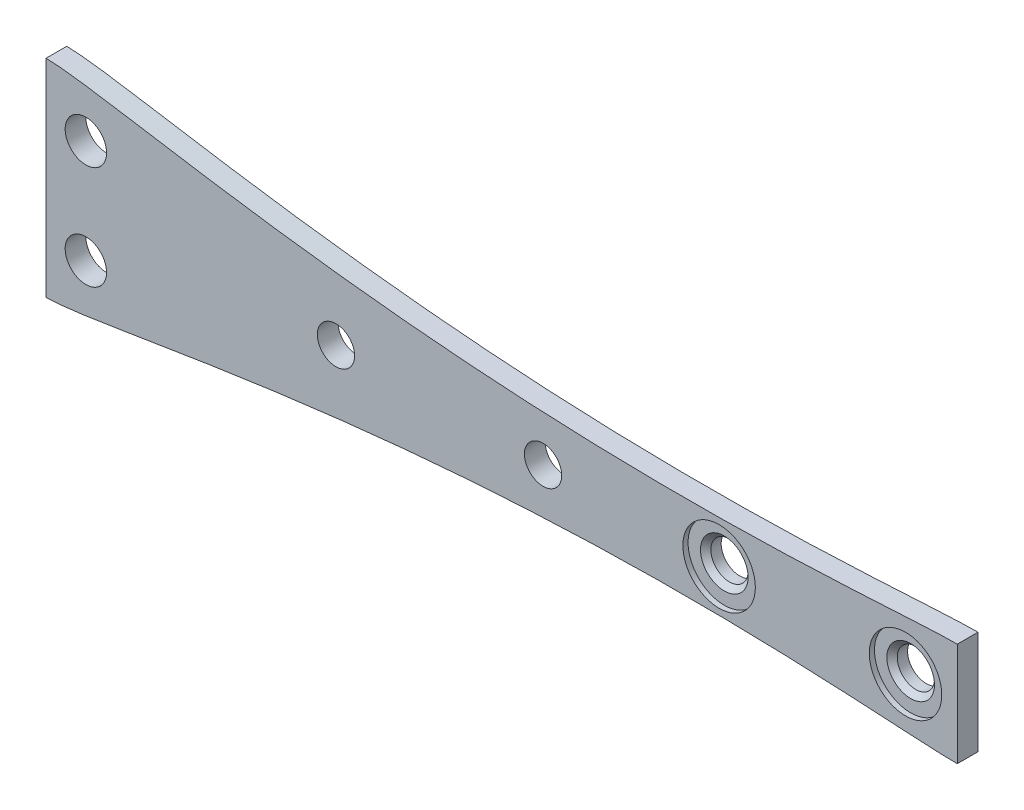
SolidWorks part; units mm, degrees
ref_plane "Plan de face" through (0, 0, 0) normal (0, 0, 1) x (1, 0, 0)
ref_plane "Plan de dessus" through (0, 0, 0) normal (0, 1, 0) x (1, 0, 0)
ref_plane "Plan de droite" through (0, 0, 0) normal (1, 0, 0) x (0, 0, -1)
sketch "Esquisse1" plane through (0, 0, 0) normal (0, 0, 1) x (1, 0, 0)
  line L0 (0, 0) -> (0, 20)
  line L1 (0, 0) -> (8, 0)
  line L2 (0, 20) -> (8, 20)
  line L3 (8, 0) -> (8, 20)
  line L4 (8, 15) -> (78, 15)
  line L5 (8, 15) -> (8, 5)
  line L6 (78, 15) -> (78, 5)
  line L7 (8, 5) -> (78, 5)
  line L8 (88, 15) -> (78, 15)
  line L9 (88, 15) -> (88, 5)
  line L10 (78, 15) -> (78, 5)
  line L11 (88, 5) -> (78, 5)
  line L12 (8, 10) -> (78, 10) construction
  line L13 (0, 20) -> (8, 20) construction
  line L14 (8, 20) -> (43, 10) construction
  line L15 (43, 10) -> (78, 15) construction
  line L16 (78, 15) -> (88, 15) construction
  line L17 (0, 0) -> (8, 0) construction
  line L18 (8, 0) -> (43, 10) construction
  line L19 (43, 10) -> (78, 5) construction
  line L20 (78, 5) -> (88, 5) construction
  circle A0 centre (3.85, 15) radius 2
  circle A1 centre (3.85, 5) radius 2
  circle A2 centre (65, 10) radius 1.8
  circle A3 centre (83, 10) radius 1.8
  circle A4 centre (28, 10) radius 1.8
  circle A5 centre (48, 10) radius 1.8
  spline S0 degree 4 poles (0, 20) (8, 20) (43, 10) (78, 15) (88, 15) knots 0 0 0 0 0 1 1 1 1 1
  spline S1 degree 4 poles (0, 0) (8, 0) (43, 10) (78, 5) (88, 5) knots 0 0 0 0 0 1 1 1 1 1
  point P0 (78, 10)
  point P12 (78, 10)
  point P16 (8, 10)
  point P17 (8, 10)
  point P43 (43, 10)
  point P44 (88, 10)
  dimension "D8" = 4
  dimension "D9" = 4
  dimension "D14" = 3.6
  dimension "D15" = 3.6
  dimension "D19" = 3.6
  dimension "D20" = 3.6
  dimension "D1" = 8
  dimension "D2" = 20
  dimension "D3" = 10
  dimension "D4" = 10
  dimension "D5" = 10
  dimension "D6" = 88
  dimension "D7" = 10
  dimension "D10" = 3.85
  dimension "D11" = 3.85
  dimension "D12" = 5
  dimension "D13" = 18
  dimension "D16" = 5
  dimension "D17" = 5
  dimension "D18" = 5
  dimension "D21" = 20
  dimension "D22" = 5
  dimension "D23" = 5
  dimension "D24" = 30
extrude "Boss.-Extru.1" add sketch "Esquisse1" along normal blind 2 contours L0 S1 L3 S0 A1 A0 | L7 S1 L10 S0 L4 L3 A5 A4 A2 | S0 L3 L4 | L3 S1 L7 | L10 S1 L9 S0 A3
sketch "Esquisse3" plane through (0, 0, 2) normal (0, 0, 1) x (1, 0, 0)
  circle A0 centre (65, 10) radius 3.5
  circle A1 centre (83, 10) radius 3.5
  dimension "D1" = 7
  dimension "D2" = 7
extrude "Enlèv. mat.-Extru.1" cut sketch "Esquisse3" against normal blind 0.5
chamfer "Chanfrein1" distance 0.5 angle 45 2 edges at (84.8, 10, 1.5) (66.8, 10, 1.5)
